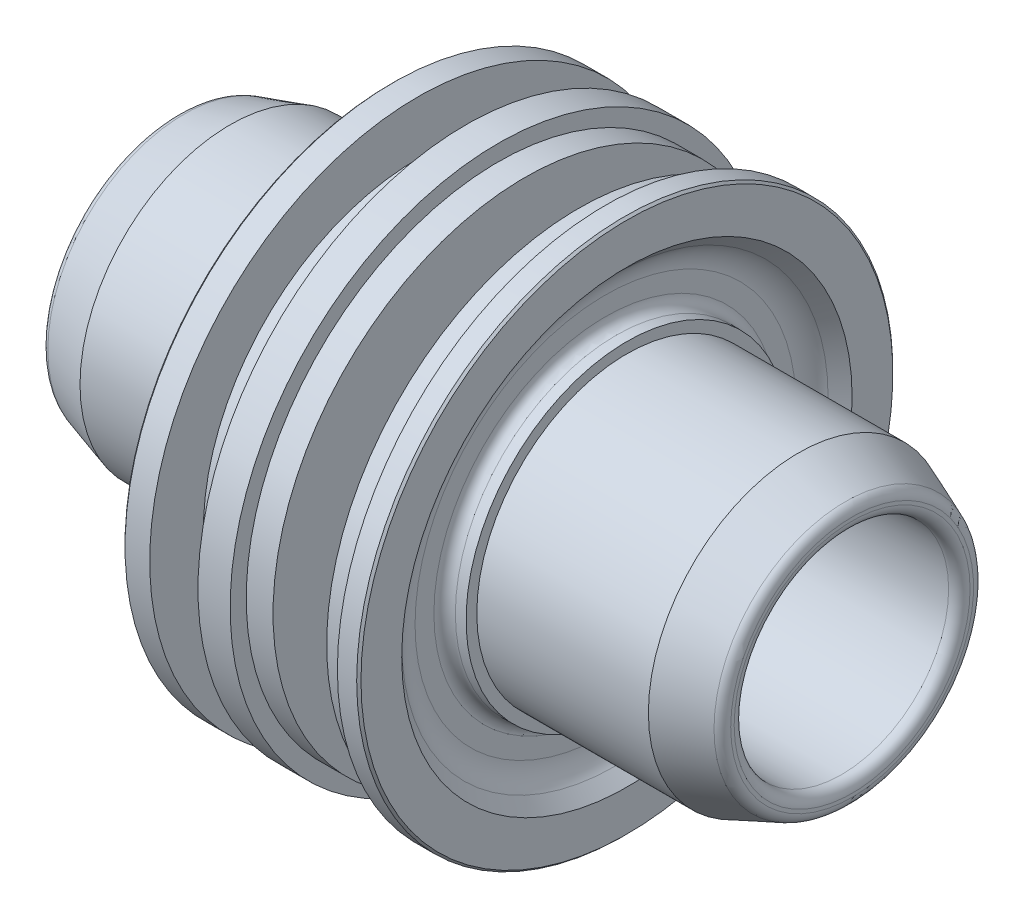
SolidWorks part; units mm, degrees
ref_plane "Płaszczyzna przednia" through (0, 0, 0) normal (0, 0, 1) x (1, 0, 0)
ref_plane "Płaszczyzna górna" through (0, 0, 0) normal (0, 1, 0) x (1, 0, 0)
ref_plane "Płaszczyzna prawa" through (0, 0, 0) normal (1, 0, 0) x (0, 0, -1)
sketch "Szkic1" plane through (0, 0, 0) normal (0, 0, 1) x (1, 0, 0)
  line L0 (-28.2802, 0) -> (42.4807, 0) construction
  line L1 (0, 6) -> (21, 6)
  line L2 (21, 6) -> (21, 10)
  line L3 (21, 10) -> (46, 10)
  line L4 (46, 10) -> (46, 12)
  line L5 (46, 12) -> (41, 14)
  line L6 (41, 14) -> (25, 14)
  line L7 (25, 14) -> (25, 25)
  line L8 (25, 25) -> (3, 25)
  line L9 (3, 25) -> (3, 14)
  line L10 (3, 14) -> (-12, 14)
  line L11 (-12, 14) -> (-17, 12.5)
  line L12 (-17, 12.5) -> (-17, 10)
  line L13 (-17, 10) -> (0, 10)
  line L14 (0, 10) -> (0, 6)
  dimension "D1" = 21
  dimension "D2" = 12
  dimension "D3" = 50
  dimension "D4" = 22
  dimension "D5" = 25
  dimension "D6" = 28
  dimension "D7" = 4
  dimension "D8" = 4
  dimension "D9" = 2
  dimension "D10" = 5
  dimension "D11" = 20
  dimension "D12" = 17
  dimension "D13" = 28
  dimension "D14" = 2.5
  dimension "D15" = 5
revolve "Obrót1" add sketch "Szkic1" angle 360 about L0
sketch "Szkic2" plane through (0, 0, 0) normal (0, 0, 1) x (1, 0, 0)
  line L0 (3, 15) -> (10.5, 15)
  line L1 (3, 25) -> (3, -25) construction
  line L2 (10.5, 15) -> (9.9347, 17.2238)
  line L3 (9.9347, 17.2238) -> (8.3332, 17.7683)
  line L4 (8.3332, 17.7683) -> (3, 18)
  line L5 (3, 18) -> (3, 15)
  line L6 (25, 25) -> (3, 25) construction
  line L7 (20.5, 23.5) -> (23, 23.5)
  line L8 (5.5, 25) -> (10, 25)
  line L9 (5.5, 25) -> (5.5, 20)
  line L10 (5.5, 20) -> (10, 20)
  line L11 (10, 25) -> (10, 20)
  line L12 (13, 25) -> (23, 25)
  line L13 (13, 25) -> (13, 23.5)
  line L14 (13, 23.5) -> (15.5, 23.5)
  line L15 (23, 25) -> (23, 23.5)
  line L17 (15.5, 23.5) -> (15.5, 15)
  line L18 (15.5, 15) -> (20.5, 15)
  line L19 (20.5, 23.5) -> (20.5, 15)
  line L20 (15.5, 23.5) -> (20.5, 15) construction
  line L21 (15.5, 15) -> (20.5, 23.5) construction
  line L22 (25, -25) -> (25, 25) construction
  line L23 (25, 15) -> (23, 15)
  line L24 (23, 15) -> (23, 19)
  line L25 (23, 19) -> (25, 21)
  line L26 (25, 21) -> (25, 15)
  point P17 (18, 19.25)
  point P25 (18, 25)
  dimension "D1" = 7.5
  dimension "D2" = 3
  dimension "D3" = 10
  dimension "D4" = 4.5
  dimension "D5" = 5
  dimension "D6" = 2.5
  dimension "D7" = 10
  dimension "D8" = 1.5
  dimension "D9" = 8.5
  dimension "D10" = 5
  dimension "D11" = 2
  dimension "D12" = 2
  dimension "D13" = 6
  dimension "D14" = 4
  dimension "D15" = 10
ref_axis "Oś1" through (25, 0, 0) along (-1, 0, 0)
revolve "Wycięcie-obrót1" cut sketch "Szkic2" angle 360 about axis through (25, 0, 0) along (-1, 0, 0)
fillet "Zaokrąglenie1" radius 1 4 edges at (-17, 0, 12.5) (-17, 0, 10) (46, 0, 12) (46, 0, 10)
fillet "Zaokrąglenie2" radius 0.5 2 edges at (0, 0, 10) (21, 0, 10)
fillet "Zaokrąglenie3" radius 1 1 edges at (23, 0, -15)
fillet "Zaokrąglenie4" radius 3 1 edges at (23, 0, -19)
fillet "Zaokrąglenie5" radius 0.5 3 edges at (8.3332, 0, -17.7683) (9.9347, 0, -17.2238) (10.5, 0, -15)
chamfer "Sfazowanie1" distance 0.2 angle 45 2 edges at (25, 0, 25) (3, 0, 25)
